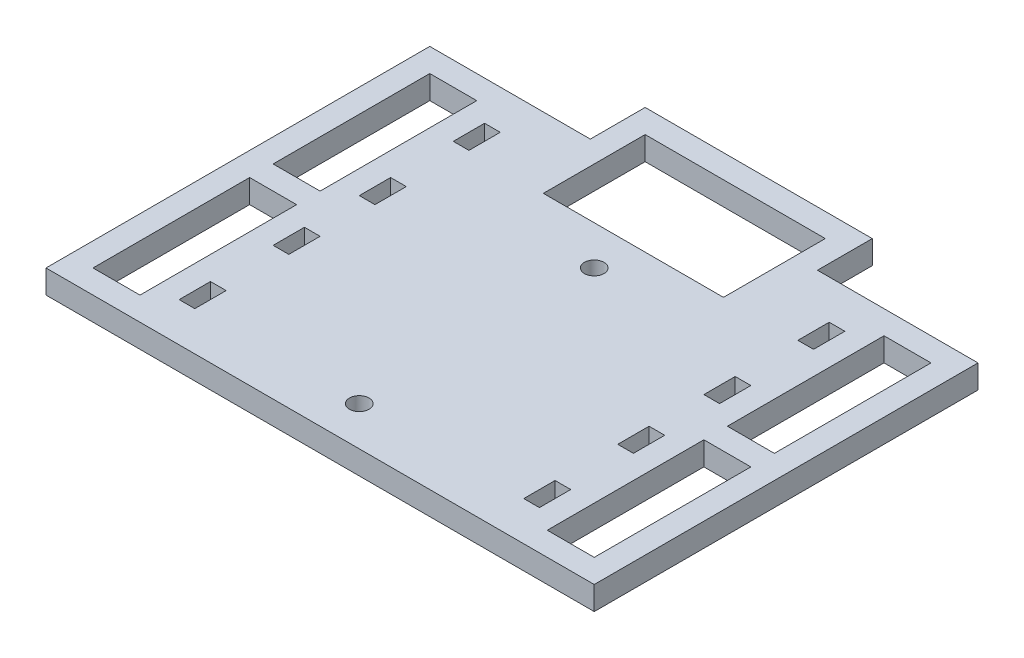
SolidWorks part; units mm, degrees
ref_plane "前视基准面" through (0, 0, 0) normal (0, 0, 1) x (1, 0, 0)
ref_plane "上视基准面" through (0, 0, 0) normal (0, 1, 0) x (1, 0, 0)
ref_plane "右视基准面" through (0, 0, 0) normal (1, 0, 0) x (0, 0, -1)
sketch "草图1" plane through (0, 0, 0) normal (0, 1, 0) x (1, 0, 0)
  line L1 (-35, 28) -> (35, 28)
  line L2 (-35, 28) -> (-35, -28)
  line L3 (-35, -28) -> (35, -28)
  line L4 (35, 28) -> (35, -28)
  line L5 (-35, 28) -> (35, -28) construction
  line L6 (-35, -28) -> (35, 28) construction
  point P0 (0, 0)
  dimension "D1" = 70
  dimension "D2" = 56
extrude "凸台-拉伸1" add sketch "草图1" along normal blind 3
sketch "草图2" plane through (0, 3, 0) normal (0, 1, 0) x (1, 0, 0)
  line L0 (0, -1000) -> (0, 49000) construction
  line L1 (-1000, -8) -> (49000, -8) construction
  line L2 (-35, -28) -> (35, -28) construction
  line L3 (-1000, 12) -> (49000, 12) construction
  line L4 (-35, 28) -> (-35, -28) construction
  line L5 (-11.5, 12) -> (11.5, 12)
  line L6 (-11.5, 12) -> (-11.5, 25)
  line L7 (-11.5, 25) -> (11.5, 25)
  line L8 (11.5, 12) -> (11.5, 25)
  line L9 (-32, -5) -> (-26, -5)
  line L10 (-32, -5) -> (-32, -25)
  line L11 (-32, -25) -> (-26, -25)
  line L12 (-26, -5) -> (-26, -25)
  line L13 (-32, 18) -> (-26, 18)
  line L14 (-32, 18) -> (-32, -2)
  line L15 (-32, -2) -> (-26, -2)
  line L16 (-26, 18) -> (-26, -2)
  line L17 (32, -25) -> (26, -25)
  line L18 (26, -5) -> (26, -25)
  line L19 (32, -5) -> (32, -25)
  line L20 (32, -5) -> (26, -5)
  line L21 (32, -2) -> (26, -2)
  line L22 (26, 18) -> (26, -2)
  line L23 (32, 18) -> (26, 18)
  line L24 (32, 18) -> (32, -2)
  line L25 (-1032, 8) -> (48968, 8) construction
  line L26 (-1032, -15) -> (48968, -15) construction
  line L27 (-23, 4) -> (-21, 4)
  line L28 (-23, 16) -> (-21, 16)
  line L29 (-23, 16) -> (-23, 12)
  line L30 (-23, 12) -> (-21, 12)
  line L31 (-21, 16) -> (-21, 12)
  line L32 (-21, 0) -> (-21, 4)
  line L33 (-23, 0) -> (-21, 0)
  line L34 (-23, 0) -> (-23, 4)
  line L35 (23, 0) -> (23, 4)
  line L36 (23, 0) -> (21, 0)
  line L37 (21, 0) -> (21, 4)
  line L38 (23, 4) -> (21, 4)
  line L39 (23, 12) -> (21, 12)
  line L40 (21, 16) -> (21, 12)
  line L41 (23, 16) -> (21, 16)
  line L42 (23, 16) -> (23, 12)
  line L43 (14.5, 28) -> (14.5, 21)
  line L44 (-35, 28) -> (-14.5, 28)
  line L45 (-35, 28) -> (-35, 21)
  line L46 (-35, 21) -> (-14.5, 21)
  line L47 (-14.5, 28) -> (-14.5, 21)
  line L48 (35, 21) -> (14.5, 21)
  line L49 (35, 28) -> (35, 21)
  line L50 (35, 28) -> (14.5, 28)
  line L51 (-23, -7) -> (-21, -7)
  line L52 (-23, -19) -> (-21, -19)
  line L53 (-23, -19) -> (-23, -23)
  line L54 (-23, -23) -> (-21, -23)
  line L55 (-21, -19) -> (-21, -23)
  line L56 (-21, -11) -> (-21, -7)
  line L57 (-23, -11) -> (-21, -11)
  line L58 (-23, -11) -> (-23, -7)
  line L59 (23, -23) -> (21, -23)
  line L60 (23, -19) -> (23, -23)
  line L61 (21, -19) -> (21, -23)
  line L62 (23, -19) -> (21, -19)
  line L63 (23, -11) -> (21, -11)
  line L64 (21, -11) -> (21, -7)
  line L65 (23, -11) -> (23, -7)
  line L66 (23, -7) -> (21, -7)
  circle A0 centre (0, 7) radius 1.25
  circle A1 centre (0, -23) radius 1.25
  point P38 (-32, 8)
  point P41 (-32, -15)
  point P62 (-29, 18)
  dimension "D10" = 2.5
  dimension "D11" = 30
  dimension "D1" = 20
  dimension "D2" = 20
  dimension "D3" = 13
  dimension "D4" = 23
  dimension "D5" = 3
  dimension "D6" = 3
  dimension "D7" = 3
  dimension "D8" = 6
  dimension "D9" = 20
  dimension "D12" = 2
  dimension "D13" = 4
  dimension "D14" = 3
  dimension "D15" = 2
  dimension "D16" = 3
  dimension "D17" = 3
  dimension "D18" = 3
  dimension "D19" = 2
  dimension "D20" = 2
  dimension "D21" = 4
extrude "切除-拉伸1" cut sketch "草图2" against normal up to next
